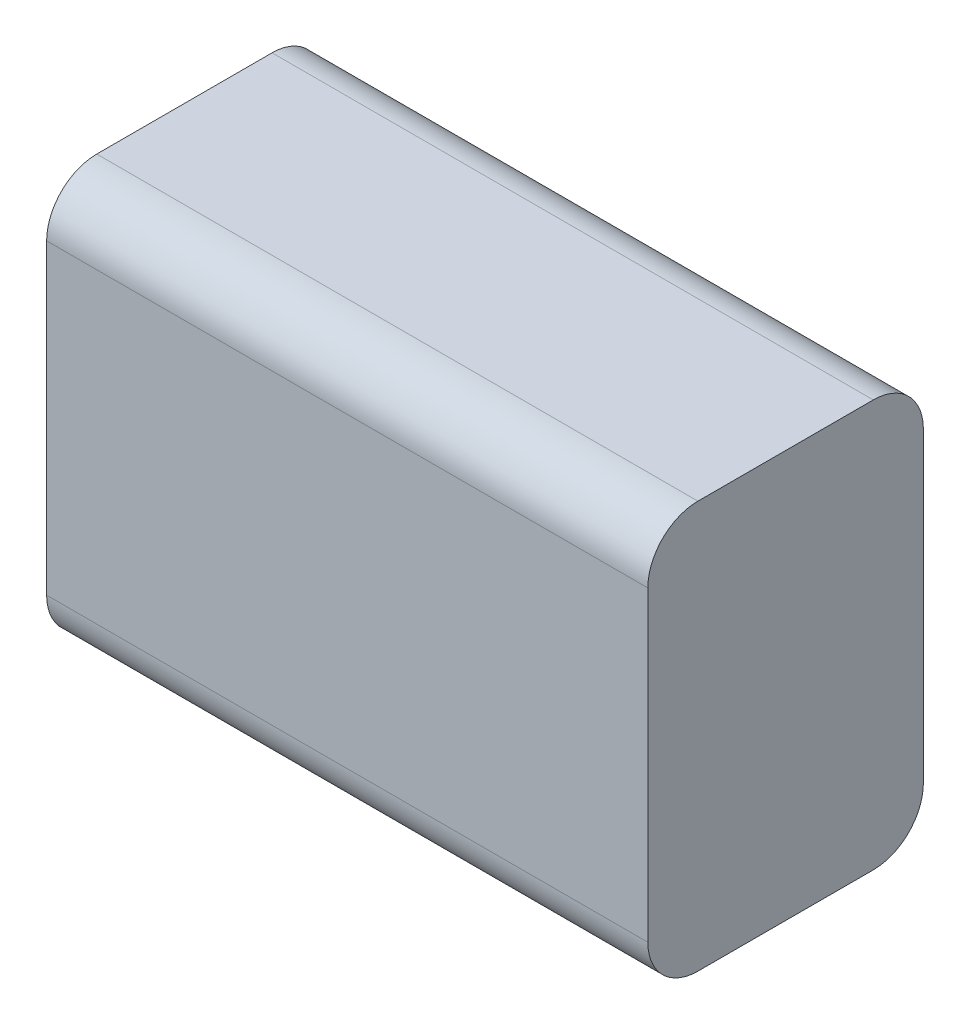
SolidWorks part; units mm, degrees
ref_plane "正面" through (0, 0, 0) normal (0, 0, 1) x (1, 0, 0)
ref_plane "平面" through (0, 0, 0) normal (0, 1, 0) x (1, 0, 0)
ref_plane "右側面" through (0, 0, 0) normal (1, 0, 0) x (0, 0, -1)
sketch "ｽｹｯﾁ1" plane through (0, 0, 0) normal (0, 0, 1) x (1, 0, 0)
  line L1 (-24, 16.25) -> (24, 16.25)
  line L2 (-24, 16.25) -> (-24, -16.25)
  line L3 (-24, -16.25) -> (24, -16.25)
  line L4 (24, 16.25) -> (24, -16.25)
  line L5 (-24, 16.25) -> (24, -16.25) construction
  line L6 (-24, -16.25) -> (24, 16.25) construction
  point P0 (0, 0)
  dimension "D1" = 48
  dimension "D2" = 32.5
extrude "ﾎﾞｽ - 押し出し1" add sketch "ｽｹｯﾁ1" along normal blind 22
fillet "ﾌｨﾚｯﾄ1" radius 4 4 edges at (0, -16.25, 0) (0, -16.25, 22) (0, 16.25, 0) (0, 16.25, 22)
